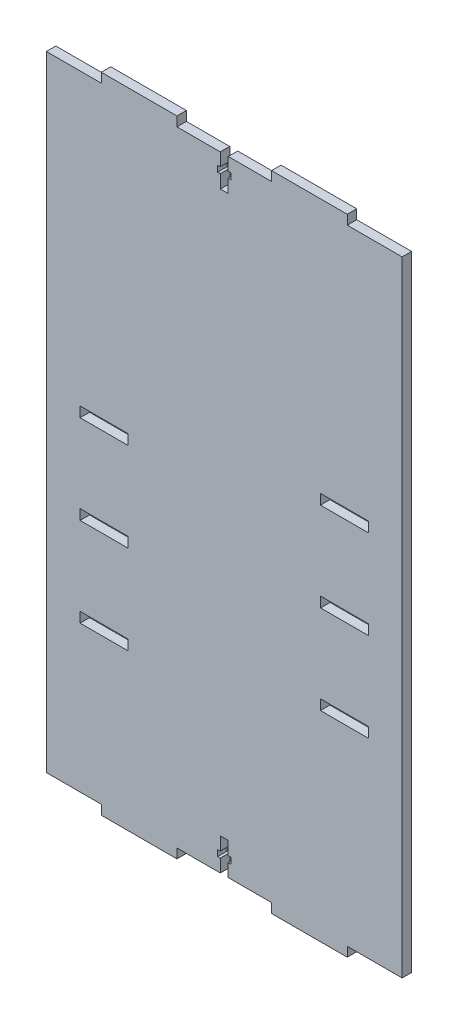
SolidWorks part; units mm, degrees
ref_plane "Front Plane" through (0, 0, 0) normal (0, 0, 1) x (1, 0, 0)
ref_plane "Top Plane" through (0, 0, 0) normal (0, 1, 0) x (1, 0, 0)
ref_plane "Right Plane" through (0, 0, 0) normal (1, 0, 0) x (0, 0, -1)
sketch "Sketch1" plane through (0, 0, 0) normal (0, 0, 1) x (1, 0, 0)
  line L0 (-94, 330) -> (-94, 267.7804) construction
  line L1 (-188, 330) -> (0, 330)
  line L2 (-188, 330) -> (-188, 0)
  line L3 (-188, 0) -> (0, 0)
  line L4 (0, 330) -> (0, 0)
  line L5 (-29, 335) -> (-69, 335)
  line L6 (-159, 330) -> (-119, 330)
  line L7 (-159, 330) -> (-159, 335)
  line L8 (-159, 335) -> (-119, 335)
  line L9 (-119, 330) -> (-119, 335)
  line L10 (-69, 330) -> (-69, 335)
  line L11 (-29, 330) -> (-69, 330)
  line L12 (-29, 330) -> (-29, 335)
  line L13 (-188, 165) -> (-29, 165) construction
  line L14 (-96.1, 330) -> (-91.9, 330)
  line L15 (-96.1, 330) -> (-96.1, 313)
  line L16 (-96.1, 313) -> (-91.9, 313)
  line L17 (-91.9, 330) -> (-91.9, 313)
  line L18 (-97.5, 323.2) -> (-90.5, 323.2)
  line L19 (-97.5, 323.2) -> (-97.5, 320)
  line L20 (-97.5, 320) -> (-90.5, 320)
  line L21 (-90.5, 323.2) -> (-90.5, 320)
  line L22 (-90.5, 6.8) -> (-90.5, 10)
  line L23 (-97.5, 10) -> (-90.5, 10)
  line L24 (-97.5, 6.8) -> (-97.5, 10)
  line L25 (-97.5, 6.8) -> (-90.5, 6.8)
  line L26 (-91.9, 0) -> (-91.9, 17)
  line L27 (-96.1, 17) -> (-91.9, 17)
  line L28 (-96.1, 0) -> (-96.1, 17)
  line L29 (-96.1, 0) -> (-91.9, 0)
  line L30 (-29, 0) -> (-29, -5)
  line L31 (-29, 0) -> (-69, 0)
  line L32 (-69, 0) -> (-69, -5)
  line L33 (-119, 0) -> (-119, -5)
  line L34 (-159, -5) -> (-119, -5)
  line L35 (-159, 0) -> (-159, -5)
  line L36 (-159, 0) -> (-119, 0)
  line L37 (-29, -5) -> (-69, -5)
  point P11 (-119, 332.5)
  point P24 (-94, 320)
  point P25 (-94, 313)
  dimension "D1" = 330
  dimension "D2" = 188
  dimension "D3" = 5
  dimension "D4" = 25
  dimension "D5" = 40
  dimension "D6" = 7
  dimension "D7" = 6.8
  dimension "D8" = 3.2
  dimension "D9" = 4.2
  dimension "D10" = 17
extrude "Boss-Extrude2" add sketch "Sketch1" along normal blind 5 contours L3 L28 L25 L24 L23 L27 L26 L22 L4 L1 L17 L18 L21 L20 L16 L15 L19 L2 | L1 L12 L5 L10 | L1 L9 L8 L7 | L37 L30 L3 L32 | L34 L33 L36 L35
sketch "Sketch2" plane through (0, 0, 0) normal (0, 0, -1) x (-1, 0, 0)
  line L48 (17.8, 194.8) -> (43.2, 194.8)
  line L49 (43.2, 194.8) -> (43.2, 200.2)
  line L50 (43.2, 200.2) -> (17.8, 200.2)
  line L51 (17.8, 200.2) -> (17.8, 194.8)
  line L52 (170.2, 176.7) -> (144.8, 176.7)
  line L53 (144.8, 176.7) -> (144.8, 171.3)
  line L54 (144.8, 171.3) -> (170.2, 171.3)
  line L55 (170.2, 171.3) -> (170.2, 176.7)
  line L56 (17.7, 147.8) -> (43.1, 147.8)
  line L57 (43.1, 147.8) -> (43.1, 153.2)
  line L58 (43.1, 153.2) -> (17.7, 153.2)
  line L59 (17.7, 153.2) -> (17.7, 147.8)
  line L60 (170.2, 129.7) -> (144.8, 129.7)
  line L61 (144.8, 129.7) -> (144.8, 124.3)
  line L62 (144.8, 124.3) -> (170.2, 124.3)
  line L63 (170.2, 124.3) -> (170.2, 129.7)
  line L64 (17.8, 100.8) -> (43.2, 100.8)
  line L65 (43.2, 100.8) -> (43.2, 106.2)
  line L66 (43.2, 106.2) -> (17.8, 106.2)
  line L67 (17.8, 106.2) -> (17.8, 100.8)
  line L68 (170.2, 82.7) -> (144.8, 82.7)
  line L69 (144.8, 82.7) -> (144.8, 77.3)
  line L70 (144.8, 77.3) -> (170.2, 77.3)
  line L71 (170.2, 77.3) -> (170.2, 82.7)
extrude "Cut-Extrude1" cut sketch "Sketch2" against normal blind 5
